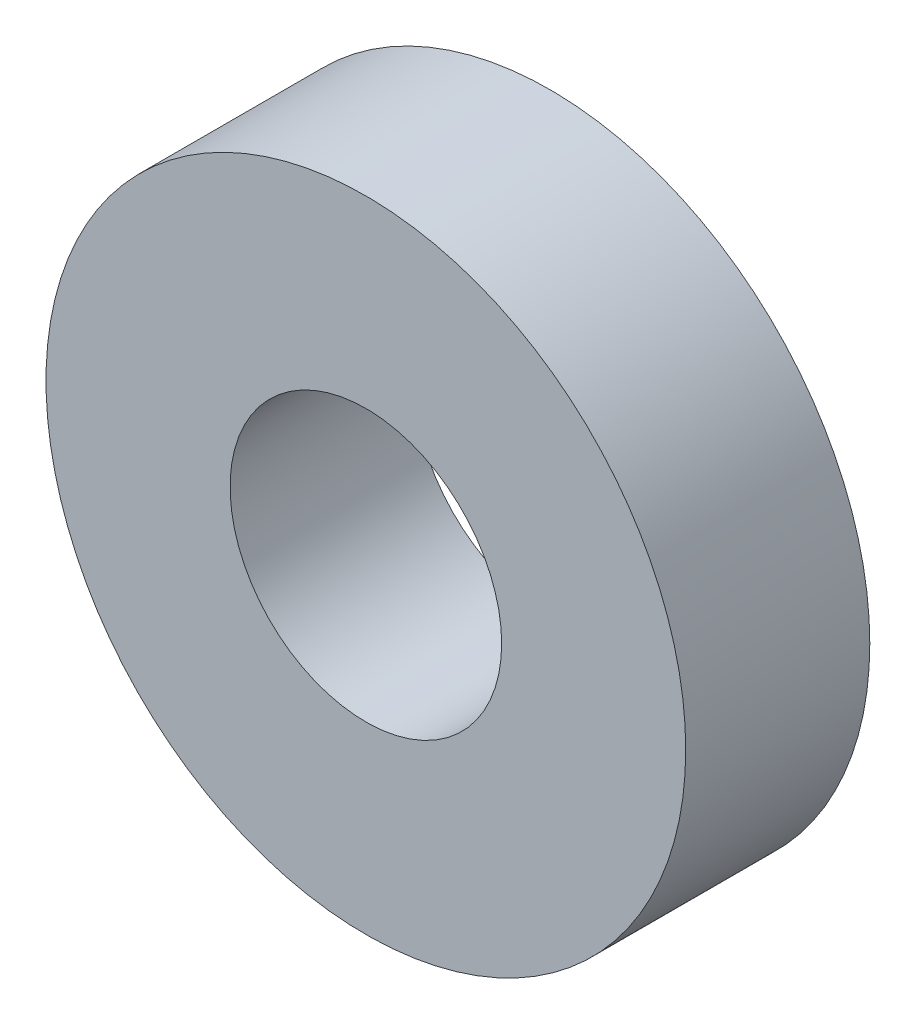
SolidWorks part; units mm, degrees
ref_plane "Front Plane" through (0, 0, 0) normal (0, 0, 1) x (1, 0, 0)
ref_plane "Top Plane" through (0, 0, 0) normal (0, 1, 0) x (1, 0, 0)
ref_plane "Right Plane" through (0, 0, 0) normal (1, 0, 0) x (0, 0, -1)
sketch "Sketch1" plane through (0, 0, 0) normal (0, 0, 1) x (1, 0, 0)
  circle A0 centre (-82.5619, 31.8106) radius 18.7371
  circle A1 centre (-82.5619, 31.8106) radius 44.1371
extrude "Boss-Extrude1" add sketch "Sketch1" along normal blind 25.4
